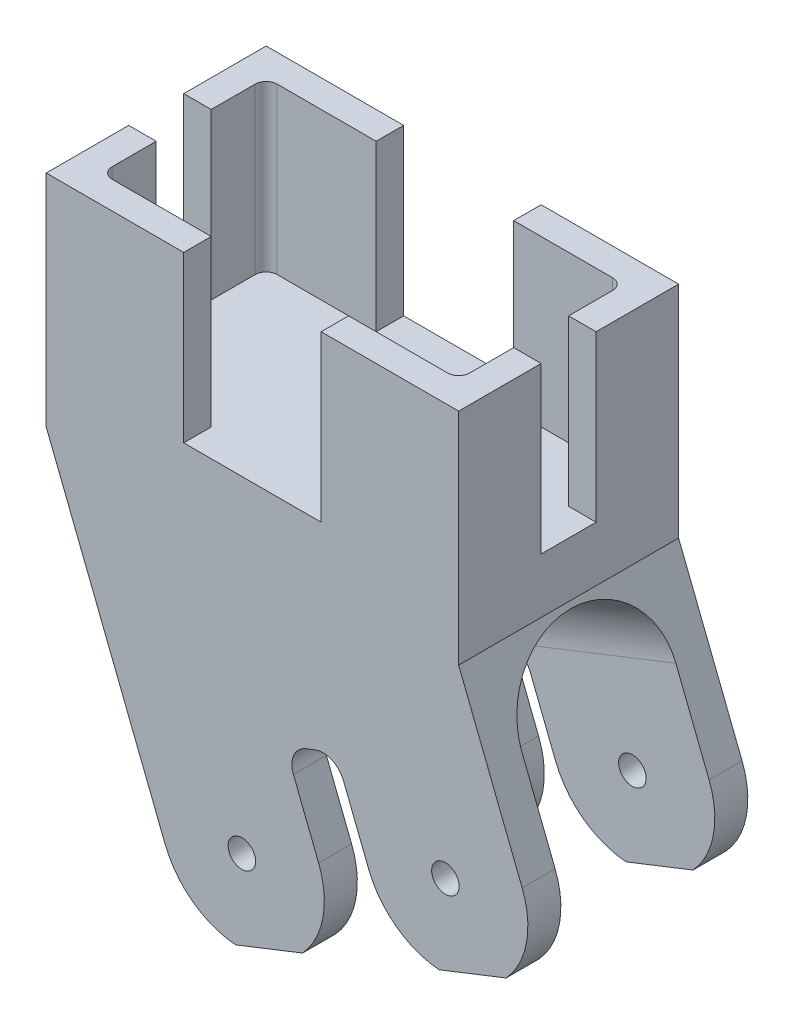
SolidWorks part; units mm, degrees
ref_plane "前视基准面" through (0, 0, 0) normal (0, 0, 1) x (1, 0, 0)
ref_plane "上视基准面" through (0, 0, 0) normal (0, 1, 0) x (1, 0, 0)
ref_plane "右视基准面" through (0, 0, 0) normal (1, 0, 0) x (0, 0, -1)
sketch "草图1" plane through (0, 0, 0) normal (0, 1, 0) x (1, 0, 0)
  line L1 (-37.5, -20) -> (37.5, -20)
  line L2 (-37.5, -20) -> (-37.5, 20)
  line L3 (-37.5, 20) -> (37.5, 20)
  line L4 (37.5, -20) -> (37.5, 20)
  line L5 (-37.5, -20) -> (37.5, 20) construction
  line L6 (-37.5, 20) -> (37.5, -20) construction
  point P0 (0, 0)
  dimension "D1" = 40
  dimension "D2" = 75
extrude "凸台-拉伸1" add sketch "草图1" along normal blind 10
sketch "草图2" plane through (0, 10, 0) normal (0, 1, 0) x (1, 0, 0)
  line L1 (-32.5, 15) -> (32.5, 15)
  line L2 (-32.5, 15) -> (-32.5, -15)
  line L3 (-32.5, -15) -> (32.5, -15)
  line L4 (32.5, 15) -> (32.5, -15)
  line L5 (-32.5, 15) -> (32.5, -15) construction
  line L6 (-32.5, -15) -> (32.5, 15) construction
  line L10 (37.5, -20) -> (37.5, 20)
  line L11 (37.5, 20) -> (-37.5, 20)
  line L12 (-37.5, 20) -> (-37.5, -20)
  line L13 (-37.5, -20) -> (37.5, -20)
  line L14 (37.5, -20) -> (37.5, 20)
  line L15 (37.5, 20) -> (-37.5, 20)
  line L16 (-37.5, 20) -> (-37.5, -20)
  line L17 (-37.5, -20) -> (37.5, -20)
  point P0 (0, 0)
  dimension "D1" = 30
  dimension "D2" = 65
  dimension "D3" = 0
extrude "凸台-拉伸2" add sketch "草图2" along normal blind 30
fillet "圆角2" radius 2 4 edges at (32.5, 25, 15) (32.5, 25, -15) (-32.5, 25, -15) (-32.5, 25, 15)
sketch "草图3" plane through (0, 40, 0) normal (0, 1, 0) x (1, 0, 0)
  line L0 (-37.5, 0) -> (37.5, 0) construction
  line L1 (-37.5, 5) -> (-32.5, 5)
  line L2 (-32.5, 13) -> (-32.5, -13) construction
  line L3 (32.5, 5) -> (37.5, 5)
  line L4 (-37.5, -20) -> (37.5, -20)
  line L5 (37.5, -20) -> (37.5, 20)
  line L6 (37.5, 20) -> (-37.5, 20)
  line L7 (-37.5, 20) -> (-37.5, -20)
  line L8 (-37.5, -20) -> (37.5, -20)
  line L9 (37.5, -20) -> (37.5, 20)
  line L10 (37.5, 20) -> (-37.5, 20)
  line L11 (-37.5, 20) -> (-37.5, -20)
  line L12 (32.5, -13) -> (32.5, 13) construction
  line L13 (32.5, -5) -> (37.5, -5)
  line L14 (-37.5, -5) -> (-32.5, -5)
  point P14 (-35, 5)
  line M9 (37.5, -20) -> (37.5, 20)
  line M11 (-37.5, 20) -> (-37.5, -20)
  line M14 (32.5, 13) -> (32.5, -13)
  line M18 (-32.5, -13) -> (-32.5, 13)
  dimension "D2" = 5
  dimension "D1" = 0
extrude "切除-拉伸1" cut sketch "草图3" against normal up to surface (30 mm away) contours L0 L11 L14 M18 | L0 L1 M11 M18 | L0 L13 L9 M14 | L0 L3 M14 M9 up to face at (0, 10, 0)
ref_plane "基准面4" through (5.0371, -12.7875, 0) normal (0.3665, -0.9304, 0) x (0, 0, -1)
sketch "草图4" plane through (5.0371, -12.7875, 0) normal (0.3665, -0.9304, 0) x (0, 0, -1)
  line L4 (20, 34.8907) -> (-20, 34.8907)
  line L5 (-20, 34.8907) -> (-20, -34.8907)
  line L6 (-20, -34.8907) -> (20, -34.8907)
  line L7 (20, -34.8907) -> (20, 34.8907)
  line L8 (20, 34.8907) -> (-20, 34.8907)
  line L9 (-20, 34.8907) -> (-20, -34.8907)
  line L10 (-20, -34.8907) -> (20, -34.8907)
  line L11 (20, -34.8907) -> (20, 34.8907)
  dimension "D1" = 0
extrude "凸台-拉伸3" add sketch "草图4" against normal up to surface (27.4876 mm away)
sketch "草图5" plane through (5.0371, -12.7875, 0) normal (0.3665, -0.9304, 0) x (0.9304, 0.3665, 0)
  line L4 (-34.8907, -20) -> (34.8907, -20)
  line L5 (34.8907, -20) -> (34.8907, 20)
  line L6 (34.8907, 20) -> (-34.8907, 20)
  line L7 (-34.8907, 20) -> (-34.8907, -20)
  line L8 (-34.8907, -20) -> (34.8907, -20)
  line L9 (34.8907, -20) -> (34.8907, 20)
  line L10 (34.8907, 20) -> (-34.8907, 20)
  line L11 (-34.8907, 20) -> (-34.8907, -20)
  dimension "D1" = 0
extrude "凸台-拉伸4" add sketch "草图5" along normal blind 45 contours L8 L9 L10 L11
sketch "草图7" plane through (32.4629, 12.7875, 0) normal (0.9304, 0.3665, 0) x (0, 0, -1)
  line L0 (-14, -28.7438) -> (-14, -58.7438)
  line L1 (14, -28.7438) -> (14, -58.7438)
  line L2 (0, 36.0662) -> (0, -36.0662) construction
  line L4 (20, -13.7438) -> (-20, -13.7438)
  line L5 (-20, -13.7438) -> (-20, -58.7438)
  line L6 (-20, -58.7438) -> (20, -58.7438)
  line L7 (20, -58.7438) -> (20, -13.7438)
  line L8 (20, -13.7438) -> (-20, -13.7438)
  line L9 (-20, -13.7438) -> (-20, -50.034)
  line L10 (-14, -58.7438) -> (14, -58.7438)
  arc A0 (14, -28.7438) -> (-14, -28.7438) centre (0, -28.7438) ccw
  point P2 (0, -28.7438)
  line M8 (-20, -58.7438) -> (20, -58.7438)
  dimension "D3" = 28
  dimension "D2" = 15
  dimension "D1" = 0
extrude "切除-拉伸2" cut sketch "草图7" along direction (-0.9304, -0.3665, 0) on the side against the normal through all contours L1 A0 L0 M8
sketch "草图9" plane through (0, 0, -14) normal (0, 0, 1) x (1, 0, 0)
  line L4 (-10.9332, -67.4437) -> (53.9926, -41.8688)
  line L5 (53.9926, -41.8688) -> (42.9975, -13.9563)
  line L6 (42.9975, -13.9563) -> (-21.9282, -39.5312)
  line L7 (-21.9282, -39.5312) -> (-10.9332, -67.4437)
  line L8 (-10.9332, -67.4437) -> (53.9926, -41.8688)
  line L9 (53.9926, -41.8688) -> (42.9975, -13.9563)
  line L10 (42.9975, -13.9563) -> (-21.9282, -39.5312)
  line L11 (-21.9282, -39.5312) -> (-10.9332, -67.4437)
  circle A0 centre (-1.9247, -49.3856) radius 2.5
  circle A1 centre (35.0885, -34.8057) radius 2.5
  point P2 (35.0885, -34.8057)
  point P4 (-1.9247, -49.3856)
  dimension "D6" = 5
  dimension "D7" = 5
  dimension "D2" = 16.5
  dimension "D3" = 15
  dimension "D4" = 16.5
  dimension "D5" = 15
  dimension "D1" = 0
extrude "切除-拉伸3" cut sketch "草图9" against normal through all and the other way through all contours A0 | A1
sketch "草图11" plane through (0, 0, -14) normal (0, 0, 1) x (1, 0, 0)
  line L0 (12.0316, -43.8881) -> (5.9843, -28.5362)
  line L1 (21.1323, -40.3032) -> (15.085, -24.9513)
  line L4 (-10.9332, -67.4437) -> (53.9926, -41.8688)
  line L5 (53.9926, -41.8688) -> (42.9975, -13.9563)
  line L6 (42.9975, -13.9563) -> (-21.9282, -39.5312)
  line L7 (-21.9282, -39.5312) -> (-10.9332, -67.4437)
  line L8 (-10.9332, -67.4437) -> (53.9926, -41.8688)
  line L9 (53.9926, -41.8688) -> (42.9975, -13.9563)
  line L10 (42.9975, -13.9563) -> (-21.9282, -39.5312)
  line L11 (-21.9282, -39.5312) -> (-10.9332, -67.4437)
  circle A0 centre (35.0885, -34.8057) radius 2.5 construction
  circle A1 centre (-1.9247, -49.3856) radius 2.5 construction
  circle A2 centre (35.0885, -34.8057) radius 2.5
  circle A3 centre (-1.9247, -49.3856) radius 2.5
  circle A4 centre (-1.9247, -49.3856) radius 15
  circle A5 centre (35.0885, -34.8057) radius 15
  line M10 (-10.9332, -67.4437) -> (53.9926, -41.8688)
  line M11 (53.9926, -41.8688) -> (42.9975, -13.9563)
  line M12 (42.9975, -13.9563) -> (-21.9282, -39.5312)
  dimension "D1" = 0
extrude "切除-拉伸4" cut sketch "草图11" against normal through all and the other way through all contours A5 L1 L0 A4 M12 M10 | A4 L11 M10 | A5 M10 M11
fillet "圆角3" radius 4 4 edges at (15.085, -24.9513, 17) (5.9843, -28.5362, 17) (15.085, -24.9513, -17) (5.9843, -28.5362, -17)
sketch "草图14" plane through (0, 40, 0) normal (0, 1, 0) x (1, 0, 0)
  line L0 (-12.5, -15) -> (-12.5, -20)
  line L1 (0, -22) -> (0, 22) construction
  line L2 (12.5, -15) -> (12.5, -20)
  line L8 (-32.5, -5) -> (-37.5, -5)
  line L9 (-37.5, -5) -> (-37.5, -20)
  line L10 (-37.5, -20) -> (37.5, -20)
  line L11 (37.5, -20) -> (37.5, -5)
  line L12 (37.5, -5) -> (32.5, -5)
  line L13 (32.5, -5) -> (32.5, -13)
  line L14 (30.5, -15) -> (-30.5, -15)
  line L15 (-32.5, -13) -> (-32.5, -5)
  line L16 (-32.5, -5) -> (-37.5, -5)
  line L17 (-37.5, -5) -> (-37.5, -20)
  line L18 (-37.5, -20) -> (37.5, -20)
  line L19 (37.5, -20) -> (37.5, -5)
  line L20 (37.5, -5) -> (32.5, -5)
  line L21 (32.5, -5) -> (32.5, -13)
  line L22 (30.5, -15) -> (-30.5, -15)
  line L23 (-32.5, -13) -> (-32.5, -5)
  arc A2 (30.5, -15) -> (32.5, -13) centre (30.5, -13) ccw
  arc A3 (-32.5, -13) -> (-30.5, -15) centre (-30.5, -13) ccw
  arc A4 (30.5, -15) -> (32.5, -13) centre (30.5, -13) ccw
  arc A5 (-32.5, -13) -> (-30.5, -15) centre (-30.5, -13) ccw
  line M14 (-37.5, -20) -> (37.5, -20)
  line M19 (30.5, -15) -> (-30.5, -15)
  dimension "D2" = 25
  dimension "D1" = 0
extrude "切除-拉伸5" cut sketch "草图14" against normal up to surface (30 mm away) contours L2 L0 M19 M14 up to face at (0, 10, 0)
mirror "镜向1" about plane through (0, 0, 0) normal (0, 0, 1) of "切除-拉伸5"
